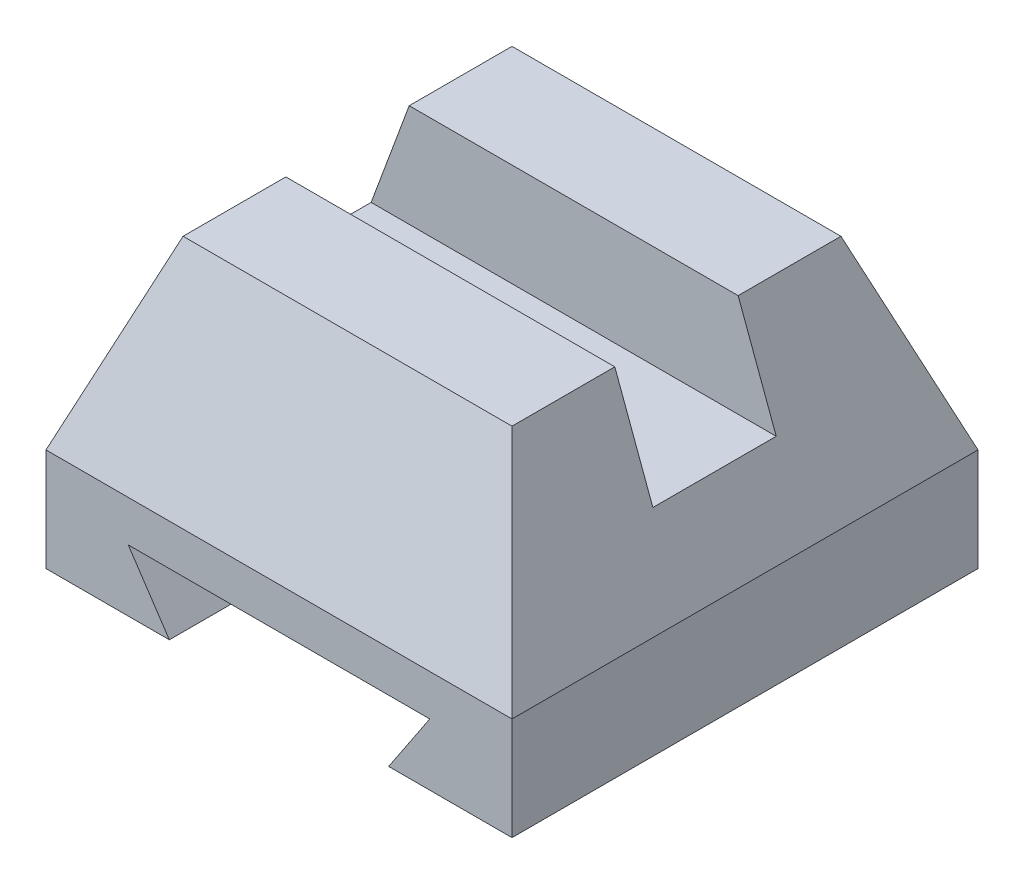
SolidWorks part; units mm, degrees
ref_plane "Front Plane" through (0, 0, 0) normal (0, 0, 1) x (1, 0, 0)
ref_plane "Top Plane" through (0, 0, 0) normal (0, 1, 0) x (1, 0, 0)
ref_plane "Right Plane" through (0, 0, 0) normal (1, 0, 0) x (0, 0, -1)
sketch "Sketch1" plane through (0, 0, 0) normal (0, 0, 1) x (1, 0, 0)
  line L0 (0, 0) -> (34, 0)
  line L1 (34, 0) -> (34, -6)
  line L2 (34, -6) -> (0, -6)
  line L3 (0, -6) -> (0, 0)
  dimension "D1" = 34
  dimension "D2" = 6
extrude "Boss-Extrude2" add sketch "Sketch1" along normal blind 34
sketch "Sketch3" plane through (0, 0, 34) normal (0, 0, 1) x (1, 0, 0)
  line L0 (34, -6) -> (34, -15)
  line L1 (34, -15) -> (16, -15)
  line L2 (34, -6) -> (22, -6)
  line L3 (0, -6) -> (34, -6) construction
  line L4 (22, -6) -> (16, -15)
  line L5 (0, 0) -> (0, -6) construction
  dimension "D1" = 18
  dimension "D2" = 22
  dimension "D3" = 9
extrude "Boss-Extrude3" add sketch "Sketch3" against normal blind 34
ref_plane "Plane3" through (0, 27, 0) normal (0, 1, 0) x (1, 0, 0)
sketch "Sketch6" plane through (0, 27, 0) normal (0, 1, 0) x (1, 0, 0)
  line L0 (0, -9) -> (0, -24)
  line L1 (0, -24) -> (24, -24)
  line L2 (24, -24) -> (24, -9)
  line L3 (24, -9) -> (0, -9)
loft "Loft2" add profiles "Sketch6" section "Sketch6" section face at (17, 0, 17)
sketch "Sketch9" plane through (0, 0, 0) normal (-1, 0, 0) x (0, 0, 1)
  line L2 (0, 0) -> (9, 0)
  line L3 (9, 0) -> (9, 27)
  line L4 (9, 27) -> (0, 0)
extrude "Cut-Extrude1" cut sketch "Sketch9" against normal blind 34
sketch "Sketch10" plane through (0, 0, 0) normal (-1, 0, 0) x (0, 0, 1)
  line L0 (0, 0) -> (0, 12)
  line L1 (0, 12) -> (9, 12)
  line L2 (9, 0) -> (9, 27) construction
  line L3 (9, 12) -> (9, 0)
  line L4 (9, 0) -> (0, 0)
  line L5 (9, 27) -> (24, 27) construction
  dimension "D1" = 15
extrude "Boss-Extrude5" add sketch "Sketch10" against normal blind 34
sketch "Sketch11" plane through (0, 0, 9) normal (0, 0, 1) x (1, 0, 0)
  line L0 (34, 0) -> (34, 12)
  line L1 (34, 12) -> (29.5556, 12)
  line L2 (29.5556, 12) -> (34, 0)
extrude "Cut-Extrude2" cut sketch "Sketch11" against normal blind 34
mirror "Mirror1" about plane through (0, -6, 34) normal (1, 0, 0) of bodies 108
mirror "Mirror2" about plane through (0, 0, 0) normal (0, 0, -1) of bodies 109
